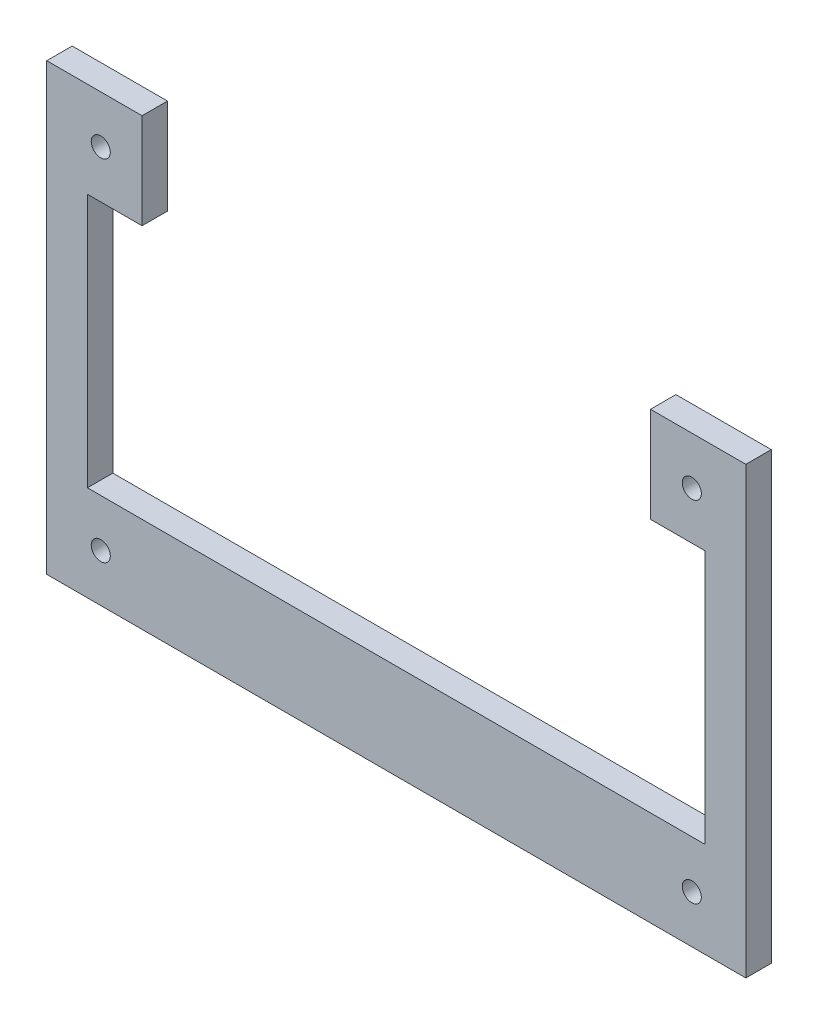
SolidWorks part; units mm, degrees
ref_plane "Front Plane" through (0, 0, 0) normal (0, 0, 1) x (1, 0, 0)
ref_plane "Top Plane" through (0, 0, 0) normal (0, 1, 0) x (1, 0, 0)
ref_plane "Right Plane" through (0, 0, 0) normal (1, 0, 0) x (0, 0, -1)
sketch "Sketch1" plane through (0, 0, 0) normal (0, 0, 1) x (1, 0, 0)
  line L1 (-55, -35) -> (55, -35)
  line L2 (-55, -35) -> (-55, 35)
  line L3 (-55, 35) -> (55, 35)
  line L4 (55, -35) -> (55, 35)
  line L5 (-55, -35) -> (55, 35) construction
  line L6 (-55, 35) -> (55, -35) construction
  point P0 (0, 0)
  dimension "D1" = 110
  dimension "D2" = 70
extrude "Plate" add sketch "Sketch1" along normal blind 4
sketch "Sketch2" plane through (0, 0, 0) normal (0, 0, -1) x (-1, 0, 0)
  line L1 (-48.6, -20) -> (48.6, -20)
  line L2 (-48.6, -20) -> (-48.6, 20)
  line L3 (-48.6, 20) -> (48.6, 20)
  line L4 (48.6, -20) -> (48.6, 20)
  line L5 (-48.6, -20) -> (48.6, 20) construction
  line L6 (-48.6, 20) -> (48.6, -20) construction
  point P0 (0, 0)
  point P5 (0, 0)
  dimension "D1" = 97.2
  dimension "D2" = 40
extrude "Screen hole" cut sketch "Sketch2" against normal through all
sketch "Sketch4" plane through (0, 0, 0) normal (0, 0, -1) x (-1, 0, 0)
  line L0 (48.6, -20) -> (48.6, 20) construction
  line L1 (-48.6, -20) -> (48.6, -20) construction
  line L2 (-48.6, 20) -> (-48.6, -20) construction
  line L3 (48.6, 20) -> (-48.6, 20) construction
  line L4 (48.6, -20) -> (48.6, 20)
  line L5 (-48.6, -20) -> (48.6, -20)
  line L6 (-48.6, 20) -> (-48.6, -20)
  line L7 (48.6, 20) -> (-48.6, 20)
  line L8 (-48.6, 20) -> (48.6, -20) construction
  line L10 (-46.5, -27.5) -> (46.5, -27.5)
  line L11 (-46.5, -27.5) -> (-46.5, 27.5)
  line L12 (-46.5, 27.5) -> (46.5, 27.5)
  line L13 (46.5, -27.5) -> (46.5, 27.5)
  line L14 (-46.5, -27.5) -> (46.5, 27.5) construction
  line L15 (-46.5, 27.5) -> (46.5, -27.5) construction
  point P3 (0, 0)
  dimension "D1" = 93
  dimension "D2" = 55
hole_wizard "Ø3.0mm Dowel Hole1" positions "3DSketch1" profile "Sketch5" hole size "Ø3.0" standard "ISO" end condition up to next
sketch3d "3DSketch1"
  point P0 (46.5, 27.5, 0)
  point P3 (-46.5, 27.5, 0)
  point P6 (-46.5, -27.5, 0)
  point P9 (46.5, -27.5, 0)
sketch "Sketch5" plane through (46.5, 27.5, 0) normal (1, 0, 0) x (0, 1, 0)
  line L0 (0, 0) -> (0, 4)
  line L1 (0, 4) -> (1.5, 4)
  line L2 (1.5, 4) -> (1.5, 0)
  line L5 (1.5, 0) -> (0, 0)
  line L11 (0, -6.35) -> (0, 107.95) construction
  dimension "Thru Hole Dia." = 3
  dimension "Thru Hole Depth" = 4
sketch "Sketch6" plane through (0, 0, 0) normal (0, 0, -1) x (-1, 0, 0)
  line L0 (48.6, 20) -> (-48.6, 20) construction
  line L1 (-40, 20) -> (40, 20)
  line L2 (-40, 20) -> (-40, 35)
  line L3 (-40, 35) -> (40, 35)
  line L4 (40, 20) -> (40, 35)
  line L5 (-55, 35) -> (55, 35) construction
  line L6 (-55, -35) -> (-55, 35) construction
  line L7 (55, 35) -> (55, -35) construction
  dimension "D1" = 15
  dimension "D2" = 15
extrude "Cut-Extrude1" cut sketch "Sketch6" against normal through all
